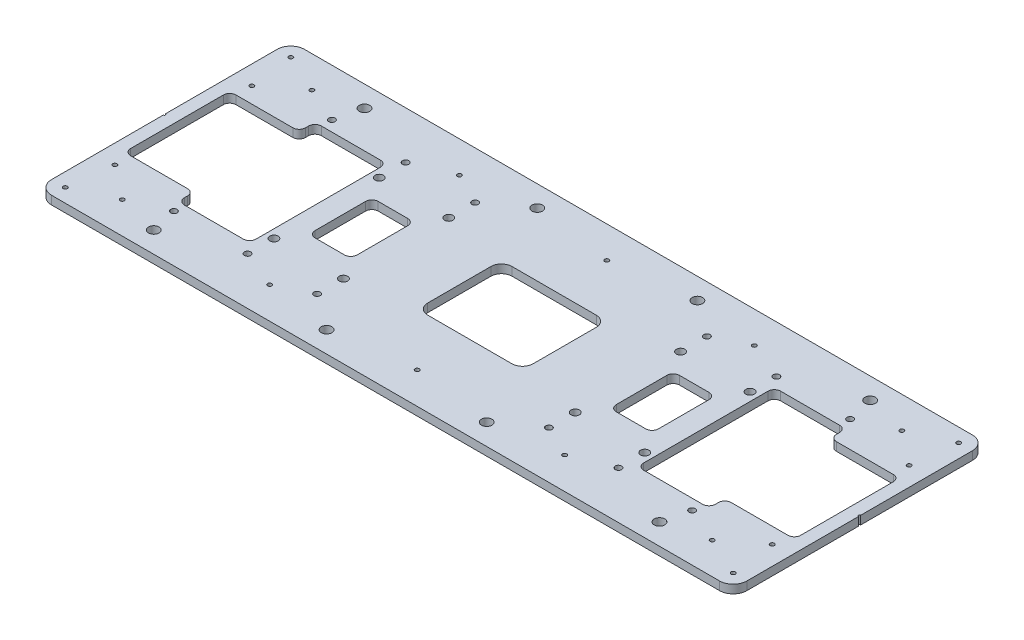
SolidWorks part; units mm, degrees
material "3.0205 (EN-AW 1200)"
ref_plane "Plan de face" through (0, 0, 0) normal (0, 0, 1) x (1, 0, 0)
ref_plane "Plan de dessus" through (0, 0, 0) normal (0, 1, 0) x (1, 0, 0)
ref_plane "Plan de droite" through (0, 0, 0) normal (1, 0, 0) x (0, 0, -1)
sketch "Esquisse1" plane through (0, 0, 0) normal (0, 1, 0) x (1, 0, 0)
  line L1 (0, 60) -> (165, 60)
  line L2 (0, 60) -> (0, -60)
  line L3 (0, -60) -> (165, -60)
  line L4 (165, 60) -> (165, -60)
  dimension "D1" = 120
  dimension "D2" = 165
extrude "Boss.-Extru.1" add sketch "Esquisse1" along normal blind 4
sketch "Esquisse2" plane through (0, 4, 0) normal (0, 1, 0) x (1, 0, 0)
  line L0 (126, -25) -> (126, -32.5)
  line L1 (92, 32.5) -> (126, 32.5)
  line L2 (92, 32.5) -> (92, -32.5)
  line L3 (92, -32.5) -> (126, -32.5)
  line L4 (126, 32.5) -> (126, 25)
  line L5 (126, 25) -> (159, 25)
  line L6 (159, 0) -> (165, 0) construction
  line L7 (126, -25) -> (159, -25)
  line L8 (159, 25) -> (159, -25)
  line L9 (165, -60) -> (165, 60) construction
  line L10 (88, 25) -> (55, -25) construction
  line L12 (81.5, -15) -> (61.5, -15)
  line L13 (81.5, -15) -> (81.5, 15)
  line L14 (81.5, 15) -> (61.5, 15)
  line L15 (61.5, -15) -> (61.5, 15)
  line L16 (81.5, -15) -> (61.5, 15) construction
  line L17 (81.5, 15) -> (61.5, -15) construction
  circle A0 centre (55, 25) radius 2
  circle A1 centre (88, 25) radius 2
  circle A2 centre (88, -25) radius 2
  circle A3 centre (55, -25) radius 2
  circle A4 centre (55, -37.5) radius 1.5
  circle A5 centre (88, -37.5) radius 1.5
  circle A6 centre (123, -37.5) radius 1.5
  circle A7 centre (123, 37.5) radius 1.5
  circle A8 centre (88, 37.5) radius 1.5
  circle A9 centre (55, 37.5) radius 1.5
  point P32 (71.5, 0)
  dimension "D6" = 4
  dimension "D7" = 50
  dimension "D8" = 33
  dimension "D9" = 4
  dimension "D10" = 3
  dimension "D11" = 35
  dimension "D12" = 75
  dimension "D1" = 6
  dimension "D2" = 50
  dimension "D3" = 65
  dimension "D4" = 39
  dimension "D5" = 34
  dimension "D13" = 20
  dimension "D14" = 30
extrude "Enlèv. mat.-Extru.1" cut sketch "Esquisse2" against normal through all
fillet "Congé1" radius 3 12 edges at (92, 2, 32.5) (126, 2, 32.5) (159, 2, 25) (159, 2, -25) (126, 2, -32.5) (92, 2, -32.5) (126, 2, 25) (126, 2, -25) (61.5, 2, 15) (81.5, 2, 15) (81.5, 2, -15) (61.5, 2, -15)
fillet "Congé2" radius 6.5 2 edges at (165, 2, -60) (165, 2, 60)
sketch "Esquisse3" plane through (0, 4, 0) normal (0, 1, 0) x (1, 0, 0)
  line L0 (0, 0) -> (165, 0) construction
  line L1 (165, -53.5) -> (165, 53.5) construction
  circle A0 centre (158.5, -53.5) radius 1
  circle A1 centre (158.5, 53.5) radius 1
  circle A2 centre (156, 32.5) radius 1
  circle A3 centre (156, -32.5) radius 1
  arc A4 (165, 53.5) -> (158.5, 60) centre (158.5, 53.5) ccw construction
  arc A5 (158.5, -60) -> (165, -53.5) centre (158.5, -53.5) ccw construction
  dimension "D1" = 2
  dimension "D2" = 65
  dimension "D3" = 2
  dimension "D4" = 9
extrude "Enlèv. mat.-Extru.2" cut sketch "Esquisse3" against normal through all
sketch "Esquisse4" plane through (0, 4, 0) normal (0, 1, 0) x (1, 0, 0)
  line L0 (0, 0) -> (165, 0) construction
  line L1 (165, -53.5) -> (165, 53.5) construction
  line L3 (0, -60) -> (158.5, -60) construction
  line L4 (0, 60) -> (0, -60) construction
  line L6 (158.5, 60) -> (0, 60) construction
  circle A0 centre (120, -50) radius 2.5
  circle A1 centre (38, -50) radius 2.5
  circle A2 centre (38, 50) radius 2.5
  circle A3 centre (120, 50) radius 2.5
  circle A4 centre (55, -25) radius 2 construction
  circle A5 centre (0, 45) radius 1
  circle A6 centre (70, 45) radius 1
  circle A7 centre (140, 45) radius 1
  circle A8 centre (140, -45) radius 1
  circle A9 centre (70, -45) radius 1
  circle A10 centre (0, -45) radius 1
  dimension "D1" = 10
  dimension "D2" = 5
  dimension "D3" = 120
  dimension "D4" = 82
  dimension "D5" = 17
  dimension "D6" = 3
  dimension "D7" = 70
  dimension "D8" = 2
  dimension "D9" = 15
extrude "Enlèv. mat.-Extru.3" cut sketch "Esquisse4" against normal through all
mirror "Symétrie1" about plane through (0, 4, -60) normal (1, 0, 0) of bodies 105 102
sketch "Esquisse6" plane through (0, 4, 0) normal (0, 1, 0) x (1, 0, 0)
  line L0 (165, -53.5) -> (165, 53.5) construction
  line L1 (-25, -20) -> (25, -20)
  line L2 (-25, -20) -> (-25, 20)
  line L3 (-25, 20) -> (25, 20)
  line L4 (25, -20) -> (25, 20)
  line L5 (-25, -20) -> (25, 20) construction
  line L6 (-25, 20) -> (25, -20) construction
  line L7 (-165, -53.5) -> (-165, 53.5) construction
  circle A0 centre (165, 0) radius 0.5
  circle A1 centre (-165, 0) radius 0.5
  point P0 (0, 0)
  dimension "D3" = 1
  dimension "D1" = 40
  dimension "D2" = 50
extrude "Enlèv. mat.-Extru.4" cut sketch "Esquisse6" against normal through all
fillet "Congé3" radius 5 4 edges at (25, 2, -20) (25, 2, 20) (-25, 2, 20) (-25, 2, -20)
